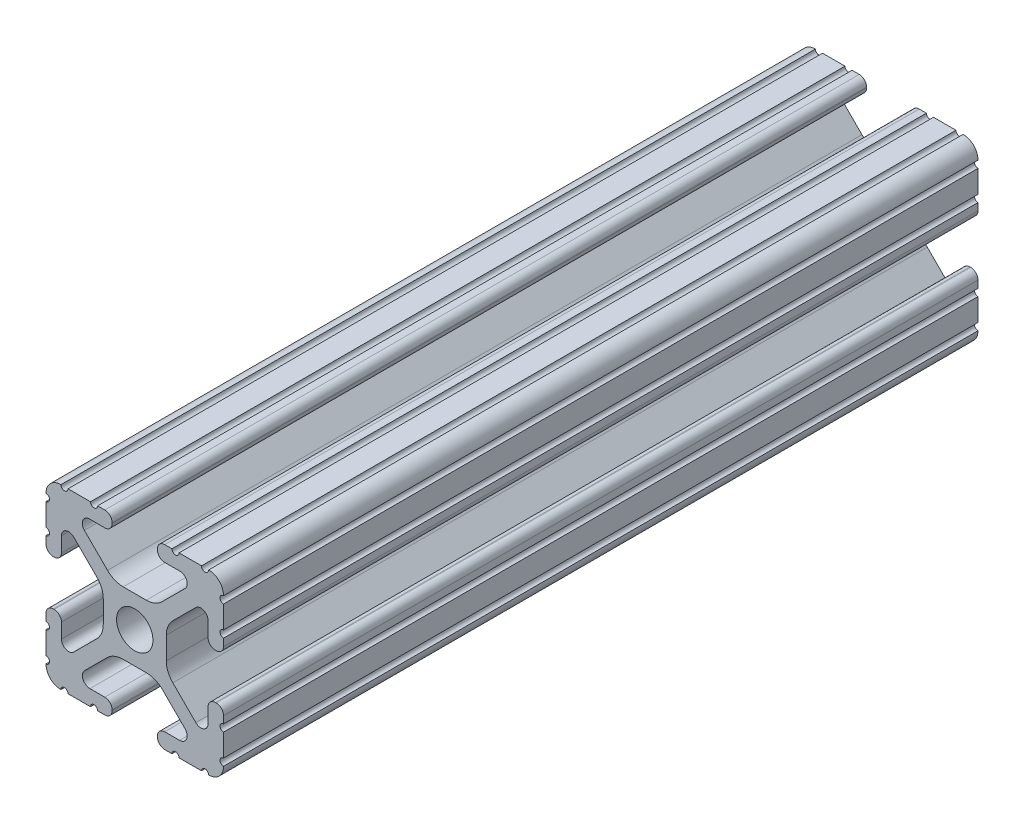
SolidWorks part; units mm, degrees
ref_plane "Front Plane" through (0, 0, 0) normal (0, 0, 1) x (1, 0, 0)
ref_plane "Top Plane" through (0, 0, 0) normal (0, 1, 0) x (1, 0, 0)
ref_plane "Right Plane" through (0, 0, 0) normal (1, 0, 0) x (0, 0, -1)
sketch "Sketch1" plane through (0, 0, 0) normal (0, 0, 1) x (1, 0, 0)
  line L88 (-7.1797, -8.6452) -> (-3.9523, -5.4237)
  line L89 (-1.7093, -4.4958) -> (1.7093, -4.4958)
  line L90 (3.9523, -5.4237) -> (7.1797, -8.6452)
  line L91 (6.4164, -10.4902) -> (4.2875, -10.4902)
  line L92 (3.2385, -11.5392) -> (3.2385, -11.651)
  line L93 (4.2875, -12.7) -> (5.3171, -12.7)
  line L94 (6.3331, -12.7) -> (9.5504, -12.7)
  line L95 (12.7, -9.5504) -> (12.7, -6.3331)
  line L96 (12.7, -5.3171) -> (12.7, -4.2875)
  line L97 (11.651, -3.2385) -> (11.5392, -3.2385)
  line L98 (10.4902, -4.2875) -> (10.4902, -6.4021)
  line L99 (8.7371, -7.1294) -> (5.441, -3.8408)
  line L100 (4.5085, -1.5932) -> (4.5085, 1.5932)
  line L101 (5.441, 3.8408) -> (8.7371, 7.1294)
  line L102 (10.4902, 6.4021) -> (10.4902, 4.2875)
  line L103 (11.5392, 3.2385) -> (11.651, 3.2385)
  line L104 (12.7, 4.2875) -> (12.7, 5.3171)
  line L105 (12.7, 6.3331) -> (12.7, 9.5504)
  line L106 (9.5504, 12.7) -> (6.3331, 12.7)
  line L107 (5.3171, 12.7) -> (4.2875, 12.7)
  line L108 (3.2385, 11.651) -> (3.2385, 11.5392)
  line L109 (4.2875, 10.4902) -> (6.4768, 10.4902)
  line L110 (7.207, 8.7244) -> (3.8983, 5.4232)
  line L111 (1.6558, 4.4958) -> (-1.6558, 4.4958)
  line L112 (-3.8983, 5.4232) -> (-7.207, 8.7244)
  line L113 (-6.4768, 10.4902) -> (-4.2875, 10.4902)
  line L114 (-3.2385, 11.5392) -> (-3.2385, 11.651)
  line L115 (-4.2875, 12.7) -> (-5.3171, 12.7)
  line L116 (-6.3331, 12.7) -> (-9.5504, 12.7)
  line L117 (-12.7, 9.5504) -> (-12.7, 6.3331)
  line L118 (-12.7, 5.3171) -> (-12.7, 4.2875)
  line L119 (-11.651, 3.2385) -> (-11.5392, 3.2385)
  line L120 (-10.4902, 4.2875) -> (-10.4902, 6.4021)
  line L121 (-8.7371, 7.1294) -> (-5.441, 3.8408)
  line L122 (-4.5085, 1.5932) -> (-4.5085, -1.5932)
  line L123 (-5.441, -3.8408) -> (-8.7371, -7.1294)
  line L124 (-10.4902, -6.4021) -> (-10.4902, -4.2875)
  line L125 (-11.5392, -3.2385) -> (-11.651, -3.2385)
  line L126 (-12.7, -4.2875) -> (-12.7, -5.3171)
  line L127 (-12.7, -6.3331) -> (-12.7, -9.5504)
  line L128 (-9.5504, -12.7) -> (-6.3331, -12.7)
  line L129 (-5.3171, -12.7) -> (-4.2875, -12.7)
  line L130 (-3.2385, -11.651) -> (-3.2385, -11.5392)
  line L131 (-4.2875, -10.4902) -> (-6.4164, -10.4902)
  circle A1 centre (0, 0) radius 2.6035
  arc A104 (-7.1797, -8.6452) -> (-6.4164, -10.4902) centre (-6.4164, -9.4098) ccw
  arc A105 (-1.7093, -4.4958) -> (-3.9523, -5.4237) centre (-1.7093, -7.6708) ccw
  arc A106 (3.9523, -5.4237) -> (1.7093, -4.4958) centre (1.7093, -7.6708) ccw
  arc A107 (6.4164, -10.4902) -> (7.1797, -8.6452) centre (6.4164, -9.4098) ccw
  arc A108 (4.2875, -10.4902) -> (3.2385, -11.5392) centre (4.2875, -11.5392) ccw
  arc A109 (3.2385, -11.651) -> (4.2875, -12.7) centre (4.2875, -11.651) ccw
  arc A110 (6.3331, -12.7) -> (5.3171, -12.7) centre (5.8251, -12.7) ccw
  arc A111 (10.5664, -12.6998) -> (9.5504, -12.7) centre (10.0584, -12.7) ccw
  arc A112 (10.5664, -12.6998) -> (12.6998, -10.5664) centre (10.5918, -10.5918) ccw
  arc A113 (12.7, -9.5504) -> (12.6998, -10.5664) centre (12.7, -10.0584) ccw
  arc A114 (12.7, -5.3171) -> (12.7, -6.3331) centre (12.7, -5.8251) ccw
  arc A115 (12.7, -4.2875) -> (11.651, -3.2385) centre (11.651, -4.2875) ccw
  arc A116 (11.5392, -3.2385) -> (10.4902, -4.2875) centre (11.5392, -4.2875) ccw
  arc A117 (8.7371, -7.1294) -> (10.4902, -6.4021) centre (9.4628, -6.4021) ccw
  arc A118 (4.5085, -1.5932) -> (5.441, -3.8408) centre (7.6835, -1.5932) ccw
  arc A119 (5.441, 3.8408) -> (4.5085, 1.5932) centre (7.6835, 1.5932) ccw
  arc A120 (10.4902, 6.4021) -> (8.7371, 7.1294) centre (9.4628, 6.4021) ccw
  arc A121 (10.4902, 4.2875) -> (11.5392, 3.2385) centre (11.5392, 4.2875) ccw
  arc A122 (11.651, 3.2385) -> (12.7, 4.2875) centre (11.651, 4.2875) ccw
  arc A123 (12.7, 6.3331) -> (12.7, 5.3171) centre (12.7, 5.8251) ccw
  arc A124 (12.6998, 10.5664) -> (12.7, 9.5504) centre (12.7, 10.0584) ccw
  arc A125 (12.6998, 10.5664) -> (10.5664, 12.6998) centre (10.5918, 10.5918) ccw
  arc A126 (9.5504, 12.7) -> (10.5664, 12.6998) centre (10.0584, 12.7) ccw
  arc A127 (5.3171, 12.7) -> (6.3331, 12.7) centre (5.8251, 12.7) ccw
  arc A128 (4.2875, 12.7) -> (3.2385, 11.651) centre (4.2875, 11.651) ccw
  arc A129 (3.2385, 11.5392) -> (4.2875, 10.4902) centre (4.2875, 11.5392) ccw
  arc A130 (7.207, 8.7244) -> (6.4768, 10.4902) centre (6.4768, 9.4563) ccw
  arc A131 (1.6558, 4.4958) -> (3.8983, 5.4232) centre (1.6558, 7.6708) ccw
  arc A132 (-3.8983, 5.4232) -> (-1.6558, 4.4958) centre (-1.6558, 7.6708) ccw
  arc A133 (-6.4768, 10.4902) -> (-7.207, 8.7244) centre (-6.4768, 9.4563) ccw
  arc A134 (-4.2875, 10.4902) -> (-3.2385, 11.5392) centre (-4.2875, 11.5392) ccw
  arc A135 (-3.2385, 11.651) -> (-4.2875, 12.7) centre (-4.2875, 11.651) ccw
  arc A136 (-6.3331, 12.7) -> (-5.3171, 12.7) centre (-5.8251, 12.7) ccw
  arc A137 (-10.5664, 12.6998) -> (-9.5504, 12.7) centre (-10.0584, 12.7) ccw
  arc A138 (-10.5664, 12.6998) -> (-12.6998, 10.5664) centre (-10.5918, 10.5918) ccw
  arc A139 (-12.7, 9.5504) -> (-12.6998, 10.5664) centre (-12.7, 10.0584) ccw
  arc A140 (-12.7, 5.3171) -> (-12.7, 6.3331) centre (-12.7, 5.8251) ccw
  arc A141 (-12.7, 4.2875) -> (-11.651, 3.2385) centre (-11.651, 4.2875) ccw
  arc A142 (-11.5392, 3.2385) -> (-10.4902, 4.2875) centre (-11.5392, 4.2875) ccw
  arc A143 (-8.7371, 7.1294) -> (-10.4902, 6.4021) centre (-9.4628, 6.4021) ccw
  arc A144 (-4.5085, 1.5932) -> (-5.441, 3.8408) centre (-7.6835, 1.5932) ccw
  arc A145 (-5.441, -3.8408) -> (-4.5085, -1.5932) centre (-7.6835, -1.5932) ccw
  arc A146 (-10.4902, -6.4021) -> (-8.7371, -7.1294) centre (-9.4628, -6.4021) ccw
  arc A147 (-10.4902, -4.2875) -> (-11.5392, -3.2385) centre (-11.5392, -4.2875) ccw
  arc A148 (-11.651, -3.2385) -> (-12.7, -4.2875) centre (-11.651, -4.2875) ccw
  arc A149 (-12.7, -6.3331) -> (-12.7, -5.3171) centre (-12.7, -5.8251) ccw
  arc A150 (-12.6998, -10.5664) -> (-12.7, -9.5504) centre (-12.7, -10.0584) ccw
  arc A151 (-12.6998, -10.5664) -> (-10.5664, -12.6998) centre (-10.5918, -10.5918) ccw
  arc A152 (-9.5504, -12.7) -> (-10.5664, -12.6998) centre (-10.0584, -12.7) ccw
  arc A153 (-5.3171, -12.7) -> (-6.3331, -12.7) centre (-5.8251, -12.7) ccw
  arc A154 (-4.2875, -12.7) -> (-3.2385, -11.651) centre (-4.2875, -11.651) ccw
  arc A155 (-3.2385, -11.5392) -> (-4.2875, -10.4902) centre (-4.2875, -11.5392) ccw
extrude "Boss-Extrude1" add sketch "Sketch1" along normal mid plane 304.8
sketch "Sketch2" plane through (0, 0, 152.4) normal (0, 0, 1) x (1, 0, 0)
  circle A0 centre (0, 0) radius 22.7926
extrude "Cut-Extrude1" cut sketch "Sketch2" against normal blind 196.85
